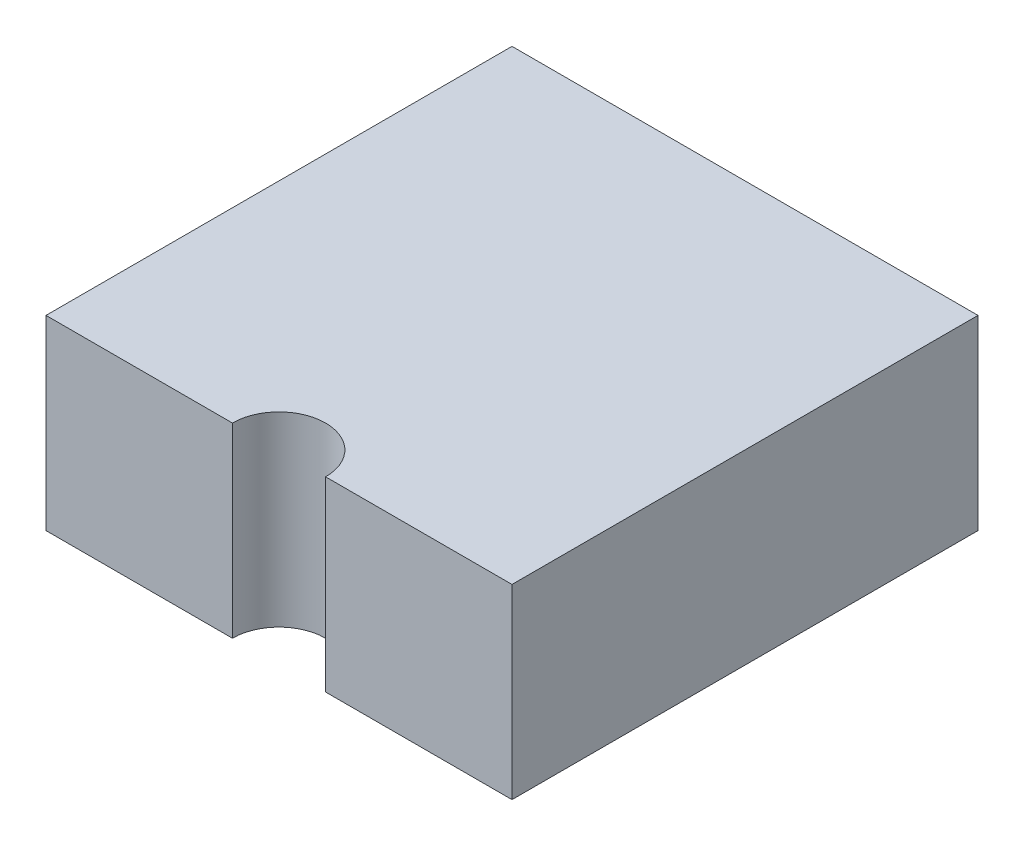
SolidWorks part; units mm, degrees
ref_plane "Front Plane" through (0, 0, 0) normal (0, 0, 1) x (1, 0, 0)
ref_plane "Top Plane" through (0, 0, 0) normal (0, 1, 0) x (1, 0, 0)
ref_plane "Right Plane" through (0, 0, 0) normal (1, 0, 0) x (0, 0, -1)
sketch "Sketch15" plane through (0, 0, 0) normal (0, 1, 0) x (1, 0, 0)
  line L0 (5, -25) -> (25, -25)
  line L1 (-25, 25) -> (25, 25)
  line L2 (-25, 25) -> (-25, -25)
  line L3 (-25, -25) -> (-5, -25)
  line L4 (25, 25) -> (25, -25)
  line L5 (-25, 25) -> (25, -25) construction
  line L6 (-25, -25) -> (25, 25) construction
  arc A0 (-5, -25) -> (5, -25) centre (0, -25) cw
  point P0 (0, 0)
  dimension "D3" = 5
  dimension "D1" = 50
  dimension "D2" = 50
extrude "Boss-Extrude3" add sketch "Sketch15" along normal blind 20
